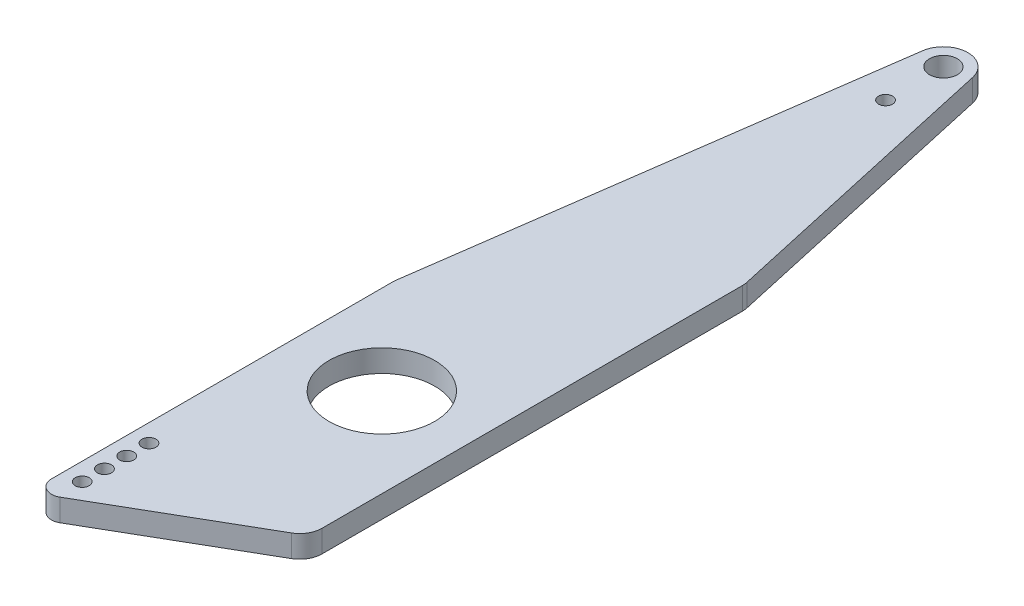
SolidWorks part; units mm, degrees
material "6061-T6 (SS)"
ref_plane "X-Y Datum" through (0, 0, 0) normal (0, 0, 1) x (1, 0, 0)
ref_plane "X-Z Datum" through (0, 0, 0) normal (0, 1, 0) x (1, 0, 0)
ref_plane "Y-Z Datum" through (0, 0, 0) normal (1, 0, 0) x (0, 0, -1)
other "Graphic1" [suppressed]
other "Graphic (Closed) -1" [suppressed]
sketch "Sketch1" plane through (0, 0, 0) normal (0, 1, 0) x (1, 0, 0)
  line L0 (25.4, -82.7357) -> (25.4, -202.7088)
  line L2 (-25.4, -229.1053) -> (-25.4, -131.2787)
  line L6 (25.4, -160.2465) -> (-25.4, -160.2465) construction
  line L28 (22.225, -208.2081) -> (-19.685, -232.4048)
  line L29 (0, 0) -> (41.91, 0) construction
  line L30 (41.91, 0) -> (0, -160.2465) construction
  line L31 (0, -160.2465) -> (0, 0) construction
  line L32 (-20.32, -219.075) -> (-20.32, -212.725) construction
  line L33 (25.2486, -81.3572) -> (6.8184, 1.5163)
  line L34 (-25.4, -131.2787) -> (-6.9178, 0.9668)
  circle A0 centre (0, 0) radius 3.9688
  circle A2 centre (0, -160.2465) radius 15.0813
  circle A6 centre (-20.32, -225.425) radius 2
  circle A7 centre (-20.32, -219.075) radius 2
  circle A8 centre (-20.32, -212.725) radius 2
  circle A9 centre (-20.32, -206.375) radius 2
  arc A10 (6.8184, 1.5163) -> (-6.9178, 0.9668) centre (0, 0) ccw
  circle A41 centre (0, -16.51) radius 2
  arc A42 (-25.4, -229.1053) -> (-19.685, -232.4048) centre (-21.59, -229.1053) ccw
  arc A43 (25.4, -202.7088) -> (22.225, -208.2081) centre (19.05, -202.7088) cw
  arc A46 (25.2486, -81.3572) -> (25.4, -82.7357) centre (19.05, -82.7357) cw
  point P21 (-20.32, -215.9)
  point P30 (25.4, -206.375)
  point P51 (25.4, -82.0382)
  dimension "D1" = 7.9375
  dimension "D4" = 30.1625
  dimension "D8" = 4
  dimension "D6" = 6.985
  dimension "D65" = 4
  dimension "D18" = 3.81
  dimension "D20" = 6.35
  dimension "D34" = 6.35
  dimension "D9" = 5.08
  dimension "D11" = 6.35
  dimension "D12" = 6.35
  dimension "D13" = 6.35
  dimension "D5" = 50.8
  dimension "D66" = 16.51
  dimension "D2" = 41.91
  dimension "D3" = 165.6363
  dimension "D7" = 215.9
  dimension "D10" = 120
  dimension "D19" = 206.375
  dimension "D23" = 187.956
extrude "Boss-Extrude1" add sketch "Sketch1" against normal blind 6.35
sketch "Sketch9" plane through (0, 0, 0) normal (0, 1, 0) x (1, 0, 0)
  line L0 (0, 0) -> (0, -162.7876)
  line L1 (0, -162.7876) -> (41.91, 0)
  line L2 (41.91, 0) -> (0, 0)
  line L3 (0, 0) -> (39.3048, -10.1191) construction
  dimension "D1" = 168.096
  dimension "D2" = 0
  dimension "D3" = 41.91
  dimension "D4" = 40.5865
  dimension "D5" = 75.563
  dimension "D6" = 162.7876
sketch "Sketch4" plane through (0, 0, 0) normal (0, 1, 0) x (1, 0, 0)
  line L0 (0, -34.29) -> (0, 0)
  line L1 (0, 0) -> (152.4, 0)
  line L2 (152.4, 0) -> (0, -34.29)
  line L3 (0, 0) -> (7.3435, -32.6377) construction
  dimension "D1" = 12.68
  dimension "D2" = 156.21
  dimension "D3" = 34.29
  dimension "D4" = 152.4
  dimension "D5" = 33.4537
sketch "Sketch10" plane through (-25.4, 0, 0) normal (-1, 0, 0) x (0, 0, 1)
  line L0 (197.3553, 0) -> (197.3553, -6.35)
  line L1 (131.2787, 0) -> (229.1053, 0) construction
  line L2 (131.2787, -6.35) -> (229.1053, -6.35) construction
  line L5 (229.1053, -6.35) -> (229.1053, 0) construction
  dimension "D1" = 31.75
split line "Split Line1"
equation "\"toePadMount\"=0.25"
equation "\"D11@Sketch1\"=\"toePadMount\""
equation "\"D12@Sketch1\"=\"toePadMount\""
equation "\"D13@Sketch1\"=\"toePadMount\""
